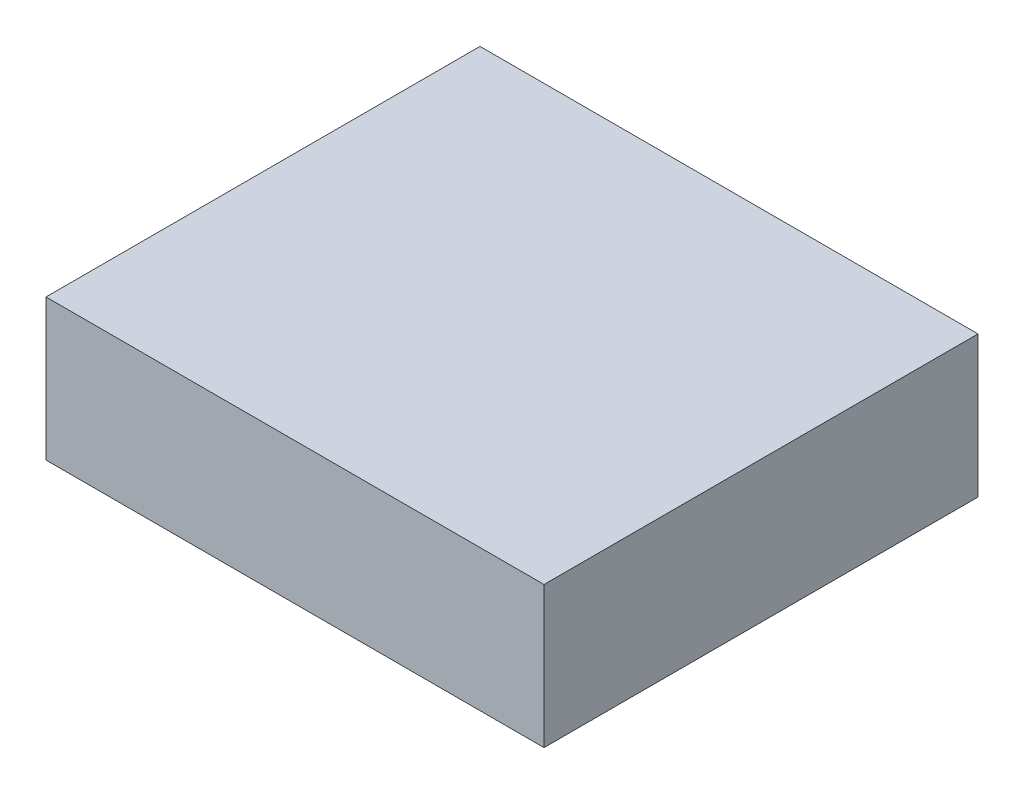
SolidWorks part; units mm, degrees
ref_plane "Front Plane" through (0, 0, 0) normal (0, 0, 1) x (1, 0, 0)
ref_plane "Top Plane" through (0, 0, 0) normal (0, 1, 0) x (1, 0, 0)
ref_plane "Right Plane" through (0, 0, 0) normal (1, 0, 0) x (0, 0, -1)
sketch "Sketch1" plane through (0, 0, 0) normal (0, 0, 1) x (1, 0, 0)
  line L1 (-5640, -800) -> (5640, -800)
  line L2 (-5640, -800) -> (-5640, 2400)
  line L3 (-5640, 2400) -> (5640, 2400)
  line L4 (5640, -800) -> (5640, 2400)
  line L5 (-5640, -800) -> (5640, 2400) construction
  line L6 (-5640, 2400) -> (5640, -800) construction
  point P0 (0, 800)
  point P6 (0, 0)
  point P7 (0, 766.3496)
  dimension "D1" = 11280
  dimension "D2" = 3200
  dimension "D3" = 800
extrude "Dimensions" add sketch "Sketch1" along normal mid plane 9830
sketch "Side" plane through (0, 0, 0) normal (1, 0, 0) x (0, 0, -1)
  line L0 (512.1667, 1122) -> (2560.8333, 1122) construction
  line L1 (-4926.9101, -6718.9606) -> (4903.0899, -6718.9606)
  line L2 (-20906.9959, -1976.1203) -> (-19882.9959, -1976.1203) construction
  line L3 (-4915, 272.8685) -> (4915, 272.8685)
  line L4 (-4915, -800) -> (-4915, 2400) construction
  line L5 (4915, -800) -> (4915, 2400) construction
  point P4 (-4915, 272.8685)
  dimension "D1" = 9830
sketch "Sketch3" plane through (0, 0, 0) normal (0, 0, 1) x (1, 0, 0)
  line L0 (5675.8957, -12496.6717) -> (5675.8957, -11472.6717) construction
